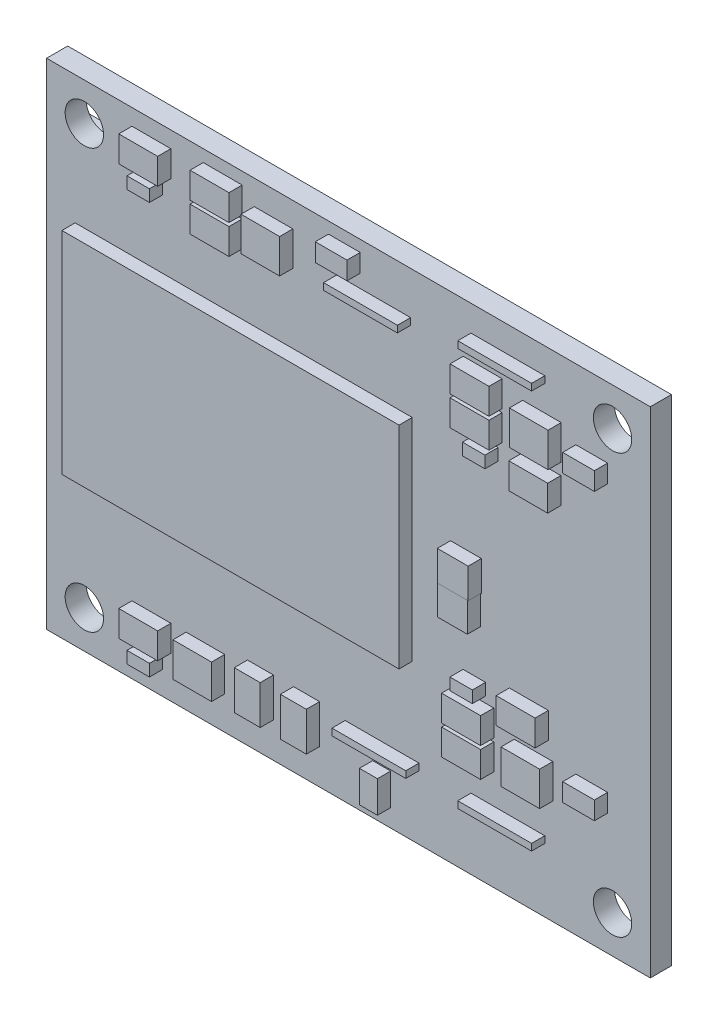
SolidWorks part; units mm, degrees
ref_plane "Front Plane" through (0, 0, 0) normal (0, 0, 1) x (1, 0, 0)
ref_plane "Top Plane" through (0, 0, 0) normal (0, 1, 0) x (1, 0, 0)
ref_plane "Right Plane" through (0, 0, 0) normal (1, 0, 0) x (0, 0, -1)
sketch "Sketch1" plane through (0, 0, 0) normal (0, 0, 1) x (1, 0, 0)
  line L0 (-0.635, -2.8575) -> (45.0725, -2.8575)
  line L1 (45.0725, -2.8575) -> (45.0725, 34.5975)
  line L2 (45.0725, 34.5975) -> (-0.635, 34.5975)
  line L3 (-0.635, 34.5975) -> (-0.635, -2.8575)
extrude "BOARD" add sketch "Sketch1" along normal blind 1.6 separate body
ref_plane "Plane1" through (0, 0, 1.6) normal (0, 0, 1) x (1, 0, 0)
sketch "Sketch2" plane through (0, 0, 1.6) normal (0, 0, 1) x (1, 0, 0)
  line L0 (32.2215, 16.0903) -> (32.2215, 13.7547)
  line L1 (32.2215, 13.7547) -> (29.9485, 13.7547)
  line L2 (29.9485, 13.7547) -> (29.9485, 16.0903)
  line L3 (29.9485, 16.0903) -> (32.2215, 16.0903)
extrude "HDRV1W64P0_1X1_193X193X447B-1" add sketch "Sketch2" along normal blind 1 separate body
sketch "Sketch3" plane through (0, 0, 1.6) normal (0, 0, 1) x (1, 0, 0)
  line L0 (29.9472, 18.2515) -> (32.2828, 18.2515)
  line L1 (32.2828, 18.2515) -> (32.2828, 15.9785)
  line L2 (32.2828, 15.9785) -> (29.9472, 15.9785)
  line L3 (29.9472, 15.9785) -> (29.9472, 18.2515)
extrude "HDRV1W64P0_1X1_193X193X447B-2" add sketch "Sketch3" along normal blind 1 separate body
sketch "Sketch4" plane through (0, 0, 1.6) normal (0, 0, 1) x (1, 0, 0)
  line L0 (20.7075, 33.7335) -> (23.1075, 33.7335)
  line L1 (23.1075, 33.7335) -> (23.1075, 32.37)
  line L2 (23.1075, 32.37) -> (20.7075, 32.37)
  line L3 (20.7075, 32.37) -> (20.7075, 33.7335)
extrude "SOD-323F-1" add sketch "Sketch4" along normal blind 1 separate body
sketch "Sketch5" plane through (0, 0, 1.6) normal (0, 0, 1) x (1, 0, 0)
  line L0 (24.0515, -1.5175) -> (24.0515, 0.8825)
  line L1 (24.0515, 0.8825) -> (25.415, 0.8825)
  line L2 (25.415, 0.8825) -> (25.415, -1.5175)
  line L3 (25.415, -1.5175) -> (24.0515, -1.5175)
extrude "SOD-323F-2" add sketch "Sketch5" along normal blind 1 separate body
sketch "Sketch6" plane through (0, 0, 1.6) normal (0, 0, 1) x (1, 0, 0)
  line L0 (39.44, 29.2885) -> (41.84, 29.2885)
  line L1 (41.84, 29.2885) -> (41.84, 27.925)
  line L2 (41.84, 27.925) -> (39.44, 27.925)
  line L3 (39.44, 27.925) -> (39.44, 29.2885)
extrude "SOD-323F-3" add sketch "Sketch6" along normal blind 1 separate body
sketch "Sketch7" plane through (0, 0, 1.6) normal (0, 0, 1) x (1, 0, 0)
  line L0 (39.44, 7.6985) -> (41.84, 7.6985)
  line L1 (41.84, 7.6985) -> (41.84, 6.335)
  line L2 (41.84, 6.335) -> (39.44, 6.335)
  line L3 (39.44, 6.335) -> (39.44, 7.6985)
extrude "SOD-323F-4" add sketch "Sketch7" along normal blind 1 separate body
sketch "Sketch8" plane through (0, 0, 1.6) normal (0, 0, 1) x (1, 0, 0)
  line L0 (26.924, 30.861) -> (21.336, 30.861)
  line L1 (21.336, 30.861) -> (21.336, 31.369)
  line L2 (21.336, 31.369) -> (26.924, 31.369)
  line L3 (26.924, 31.369) -> (26.924, 30.861)
extrude "1X03-CLEANBIG-1" add sketch "Sketch8" along normal blind 1 separate body
sketch "Sketch9" plane through (0, 0, 1.6) normal (0, 0, 1) x (1, 0, 0)
  line L0 (21.971, 2.4765) -> (27.559, 2.4765)
  line L1 (27.559, 2.4765) -> (27.559, 1.9685)
  line L2 (27.559, 1.9685) -> (21.971, 1.9685)
  line L3 (21.971, 1.9685) -> (21.971, 2.4765)
extrude "1X03-CLEANBIG-2" add sketch "Sketch9" along normal blind 1 separate body
sketch "Sketch10" plane through (0, 0, 1.6) normal (0, 0, 1) x (1, 0, 0)
  line L0 (31.496, 32.639) -> (37.084, 32.639)
  line L1 (37.084, 32.639) -> (37.084, 32.131)
  line L2 (37.084, 32.131) -> (31.496, 32.131)
  line L3 (31.496, 32.131) -> (31.496, 32.639)
extrude "1X03-CLEANBIG-3" add sketch "Sketch10" along normal blind 1 separate body
sketch "Sketch11" plane through (0, 0, 1.6) normal (0, 0, 1) x (1, 0, 0)
  line L0 (31.496, 2.4765) -> (37.084, 2.4765)
  line L1 (37.084, 2.4765) -> (37.084, 1.9685)
  line L2 (37.084, 1.9685) -> (31.496, 1.9685)
  line L3 (31.496, 1.9685) -> (31.496, 2.4765)
extrude "1X03-CLEANBIG-4" add sketch "Sketch11" along normal blind 1 separate body
sketch "Sketch12" plane through (0, 0, 1.6) normal (0, 0, 1) x (1, 0, 0)
  line L0 (8.1525, 30.9308) -> (8.1525, 30.03)
  line L1 (8.1525, 30.03) -> (6.4525, 30.03)
  line L2 (6.4525, 30.03) -> (6.4525, 30.9308)
  line L3 (6.4525, 30.9308) -> (8.1525, 30.9308)
extrude "CHIP-LED0603-1" add sketch "Sketch12" along normal blind 1 separate body
sketch "Sketch13" plane through (0, 0, 1.6) normal (0, 0, 1) x (1, 0, 0)
  line L0 (8.1525, -0.1842) -> (8.1525, -1.085)
  line L1 (8.1525, -1.085) -> (6.4525, -1.085)
  line L2 (6.4525, -1.085) -> (6.4525, -0.1842)
  line L3 (6.4525, -0.1842) -> (8.1525, -0.1842)
extrude "CHIP-LED0603-2" add sketch "Sketch13" along normal blind 1 separate body
sketch "Sketch14" plane through (0, 0, 1.6) normal (0, 0, 1) x (1, 0, 0)
  line L0 (31.8525, 25.2667) -> (31.8525, 26.1675)
  line L1 (31.8525, 26.1675) -> (33.5525, 26.1675)
  line L2 (33.5525, 26.1675) -> (33.5525, 25.2667)
  line L3 (33.5525, 25.2667) -> (31.8525, 25.2667)
extrude "CHIP-LED0603-3" add sketch "Sketch14" along normal blind 1 separate body
sketch "Sketch15" plane through (0, 0, 1.6) normal (0, 0, 1) x (1, 0, 0)
  line L0 (30.9, 9.3917) -> (30.9, 10.2925)
  line L1 (30.9, 10.2925) -> (32.6, 10.2925)
  line L2 (32.6, 10.2925) -> (32.6, 9.3917)
  line L3 (32.6, 9.3917) -> (30.9, 9.3917)
extrude "CHIP-LED0603-4" add sketch "Sketch15" along normal blind 1 separate body
sketch "Sketch16" plane through (0, 0, 1.6) normal (0, 0, 1) x (1, 0, 0)
  line L0 (15.0876, 32.7279) -> (18.0086, 32.7279)
  line L1 (18.0086, 32.7279) -> (18.0086, 30.1371)
  line L2 (18.0086, 30.1371) -> (15.0876, 30.1371)
  line L3 (15.0876, 30.1371) -> (15.0876, 32.7279)
extrude "SOT23-1" add sketch "Sketch16" along normal blind 1 separate body
sketch "Sketch17" plane through (0, 0, 1.6) normal (0, 0, 1) x (1, 0, 0)
  line L0 (12.8524, -0.3429) -> (9.9314, -0.3429)
  line L1 (9.9314, -0.3429) -> (9.9314, 2.2479)
  line L2 (9.9314, 2.2479) -> (12.8524, 2.2479)
  line L3 (12.8524, 2.2479) -> (12.8524, -0.3429)
extrude "SOT23-2" add sketch "Sketch17" along normal blind 1 separate body
sketch "Sketch18" plane through (0, 0, 1.6) normal (0, 0, 1) x (1, 0, 0)
  line L0 (35.4076, 30.1879) -> (38.3286, 30.1879)
  line L1 (38.3286, 30.1879) -> (38.3286, 27.5971)
  line L2 (38.3286, 27.5971) -> (35.4076, 27.5971)
  line L3 (35.4076, 27.5971) -> (35.4076, 30.1879)
extrude "SOT23-3" add sketch "Sketch18" along normal blind 1 separate body
sketch "Sketch19" plane through (0, 0, 1.6) normal (0, 0, 1) x (1, 0, 0)
  line L0 (34.7726, 7.6454) -> (37.6936, 7.6454)
  line L1 (37.6936, 7.6454) -> (37.6936, 5.0546)
  line L2 (37.6936, 5.0546) -> (34.7726, 5.0546)
  line L3 (34.7726, 5.0546) -> (34.7726, 7.6454)
extrude "SOT23-4" add sketch "Sketch19" along normal blind 1 separate body
sketch "Sketch20" plane through (0, 0, 1.6) normal (0, 0, 1) x (1, 0, 0)
  line L0 (11.227, 31.463) -> (14.173, 31.463)
  line L1 (14.173, 31.463) -> (14.173, 29.497)
  line L2 (14.173, 29.497) -> (11.227, 29.497)
  line L3 (11.227, 29.497) -> (11.227, 31.463)
extrude "R0603-1" add sketch "Sketch20" along normal blind 1 separate body
sketch "Sketch21" plane through (0, 0, 1.6) normal (0, 0, 1) x (1, 0, 0)
  line L0 (11.227, 33.6855) -> (14.173, 33.6855)
  line L1 (14.173, 33.6855) -> (14.173, 31.7195)
  line L2 (14.173, 31.7195) -> (11.227, 31.7195)
  line L3 (11.227, 31.7195) -> (11.227, 33.6855)
extrude "R0603-2" add sketch "Sketch21" along normal blind 1 separate body
sketch "Sketch22" plane through (0, 0, 1.6) normal (0, 0, 1) x (1, 0, 0)
  line L0 (5.8295, 33.368) -> (8.7755, 33.368)
  line L1 (8.7755, 33.368) -> (8.7755, 31.402)
  line L2 (8.7755, 31.402) -> (5.8295, 31.402)
  line L3 (5.8295, 31.402) -> (5.8295, 33.368)
extrude "R0603-3" add sketch "Sketch22" along normal blind 1 separate body
sketch "Sketch23" plane through (0, 0, 1.6) normal (0, 0, 1) x (1, 0, 0)
  line L0 (18.067, -0.203) -> (18.067, 2.743)
  line L1 (18.067, 2.743) -> (20.033, 2.743)
  line L2 (20.033, 2.743) -> (20.033, -0.203)
  line L3 (20.033, -0.203) -> (18.067, -0.203)
extrude "R0603-4" add sketch "Sketch23" along normal blind 1 separate body
sketch "Sketch24" plane through (0, 0, 1.6) normal (0, 0, 1) x (1, 0, 0)
  line L0 (14.5745, -0.203) -> (14.5745, 2.743)
  line L1 (14.5745, 2.743) -> (16.5405, 2.743)
  line L2 (16.5405, 2.743) -> (16.5405, -0.203)
  line L3 (16.5405, -0.203) -> (14.5745, -0.203)
extrude "R0603-5" add sketch "Sketch24" along normal blind 1 separate body
sketch "Sketch25" plane through (0, 0, 1.6) normal (0, 0, 1) x (1, 0, 0)
  line L0 (5.8295, 2.253) -> (8.7755, 2.253)
  line L1 (8.7755, 2.253) -> (8.7755, 0.287)
  line L2 (8.7755, 0.287) -> (5.8295, 0.287)
  line L3 (5.8295, 0.287) -> (5.8295, 2.253)
extrude "R0603-6" add sketch "Sketch25" along normal blind 1 separate body
sketch "Sketch26" plane through (0, 0, 1.6) normal (0, 0, 1) x (1, 0, 0)
  line L0 (30.912, 30.828) -> (33.858, 30.828)
  line L1 (33.858, 30.828) -> (33.858, 28.862)
  line L2 (33.858, 28.862) -> (30.912, 28.862)
  line L3 (30.912, 28.862) -> (30.912, 30.828)
extrude "R0603-7" add sketch "Sketch26" along normal blind 1 separate body
sketch "Sketch27" plane through (0, 0, 1.6) normal (0, 0, 1) x (1, 0, 0)
  line L0 (38.303, 24.7345) -> (35.357, 24.7345)
  line L1 (35.357, 24.7345) -> (35.357, 26.7005)
  line L2 (35.357, 26.7005) -> (38.303, 26.7005)
  line L3 (38.303, 26.7005) -> (38.303, 24.7345)
extrude "R0603-8" add sketch "Sketch27" along normal blind 1 separate body
sketch "Sketch28" plane through (0, 0, 1.6) normal (0, 0, 1) x (1, 0, 0)
  line L0 (33.858, 26.6395) -> (30.912, 26.6395)
  line L1 (30.912, 26.6395) -> (30.912, 28.6055)
  line L2 (30.912, 28.6055) -> (33.858, 28.6055)
  line L3 (33.858, 28.6055) -> (33.858, 26.6395)
extrude "R0603-9" add sketch "Sketch28" along normal blind 1 separate body
sketch "Sketch29" plane through (0, 0, 1.6) normal (0, 0, 1) x (1, 0, 0)
  line L0 (30.277, 6.698) -> (33.223, 6.698)
  line L1 (33.223, 6.698) -> (33.223, 4.732)
  line L2 (33.223, 4.732) -> (30.277, 4.732)
  line L3 (30.277, 4.732) -> (30.277, 6.698)
extrude "R0603-10" add sketch "Sketch29" along normal blind 1 separate body
sketch "Sketch30" plane through (0, 0, 1.6) normal (0, 0, 1) x (1, 0, 0)
  line L0 (37.3505, 8.8595) -> (34.4045, 8.8595)
  line L1 (34.4045, 8.8595) -> (34.4045, 10.8255)
  line L2 (34.4045, 10.8255) -> (37.3505, 10.8255)
  line L3 (37.3505, 10.8255) -> (37.3505, 8.8595)
extrude "R0603-11" add sketch "Sketch30" along normal blind 1 separate body
sketch "Sketch31" plane through (0, 0, 1.6) normal (0, 0, 1) x (1, 0, 0)
  line L0 (33.223, 6.9545) -> (30.277, 6.9545)
  line L1 (30.277, 6.9545) -> (30.277, 8.9205)
  line L2 (30.277, 8.9205) -> (33.223, 8.9205)
  line L3 (33.223, 8.9205) -> (33.223, 6.9545)
extrude "R0603-12" add sketch "Sketch31" along normal blind 1 separate body
sketch "Sketch32" plane through (0, 0, 1.6) normal (0, 0, 1) x (1, 0, 0)
  line L0 (1.5275, 24.884) -> (27.0475, 24.884)
  line L1 (27.0475, 24.884) -> (27.0475, 8.89)
  line L2 (27.0475, 8.89) -> (1.5275, 8.89)
  line L3 (1.5275, 8.89) -> (1.5275, 24.884)
extrude "HDRVR10W64P254_1X10_2540X254X254B-1" add sketch "Sketch32" along normal blind 1 separate body
sketch "Sketch33" plane through (0, 0, 0) normal (0, 0, 1) x (1, 0, 0)
  line L0 (38.795, 29.964) -> (-0.695, 29.964)
  line L1 (-0.695, 29.964) -> (-0.695, 3.75)
  line L2 (-0.695, 3.75) -> (38.795, 3.75)
  line L3 (38.795, 3.75) -> (38.795, 29.964)
extrude "HDRVR16W64P2286X254_2X8_2032X2540X254B-1" add sketch "Sketch33" against normal blind 1 separate body
sketch "Sketch34" plane through (0, 0, 0) normal (0, 0, 1) x (1, 0, 0)
  line L0 (39.886, 24.5075) -> (39.886, 9.1475)
  line L1 (39.886, 9.1475) -> (43.24, 9.1475)
  line L2 (43.24, 9.1475) -> (43.24, 24.5075)
  line L3 (43.24, 24.5075) -> (39.886, 24.5075)
extrude "HDRVR6W64P254_1X6_1524X254X762B-1" add sketch "Sketch34" against normal blind 1 separate body
sketch "Sketch35" plane through (0, 0, 1.6) normal (0, 0, 1) x (1, 0, 0)
  line L0 (45.0725, 34.5975) -> (-0.635, 34.5975) construction
  line L2 (-0.635, 34.5975) -> (-0.635, -2.8575) construction
  line L3 (22.2188, 34.5975) -> (22.2188, -2.8575) construction
  line L4 (-0.635, 15.87) -> (45.0725, 15.87) construction
  line L7 (-0.635, 34.5975) -> (-0.635, -2.8575)
  line L8 (-0.635, -2.8575) -> (45.0725, -2.8575)
  line L9 (45.0725, -2.8575) -> (45.0725, 34.5975)
  line L10 (45.0725, 34.5975) -> (-0.635, 34.5975)
  line L11 (-0.635, 34.5975) -> (-0.635, -2.8575) construction
  line L12 (-0.635, -2.8575) -> (45.0725, -2.8575) construction
  line L13 (45.0725, -2.8575) -> (45.0725, 34.5975) construction
  line L14 (45.0725, 34.5975) -> (-0.635, 34.5975) construction
  circle A0 centre (2.2225, 31.74) radius 1.4529
  circle A1 centre (42.215, 31.74) radius 1.4529
  circle A2 centre (42.215, 0) radius 1.4529
  circle A3 centre (2.2225, 0) radius 1.4529
  dimension "D1" = 2.9058
  dimension "D2" = 2.8575
  dimension "D3" = 2.8575
  dimension "D4" = 0
extrude "Cut-Extrude1" cut sketch "Sketch35" against normal through all
